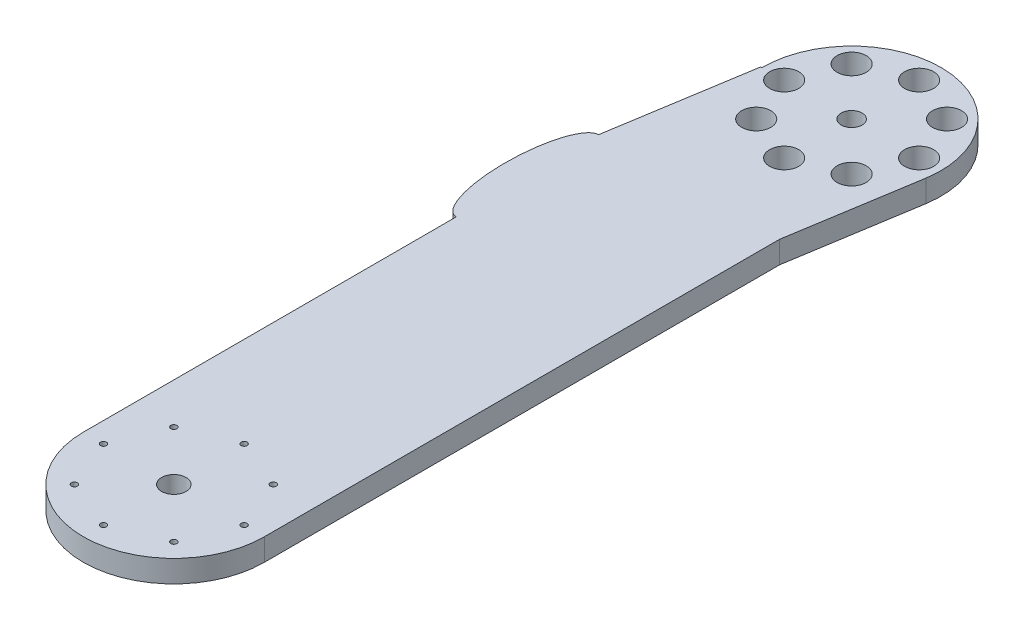
SolidWorks part; units mm, degrees
ref_plane "Plano frontal" through (0, 0, 0) normal (0, 0, 1) x (1, 0, 0)
ref_plane "Plano superior" through (0, 0, 0) normal (0, 1, 0) x (1, 0, 0)
ref_plane "Plano direito" through (0, 0, 0) normal (1, 0, 0) x (0, 0, -1)
sketch "Esboço1" plane through (0, 0, 0) normal (0, 1, 0) x (1, 0, 0)
  line L0 (-40.8421, 0) -> (-40.8421, 168.2347)
  line L1 (40.8421, 0) -> (40.8421, 168.2347)
  line L2 (40.8421, 232.4315) -> (51.0009, 295.8325)
  line L3 (40.8421, 168.2347) -> (40.8421, 232.4315)
  line L4 (-40.8421, 232.4315) -> (-30.751, 295.4098)
  line L5 (51.0009, 295.8325) -> (50.4521, 295.8297)
  line L6 (-30.2022, 295.4126) -> (-30.751, 295.4098)
  circle A0 centre (0, 0) radius 40.8421
  circle A11 centre (10.125, 295.6212) radius 40.3277
  ellipse E1 centre (-40.8421, 200.3331) end of major axis (-40.8421, 232.4315) minor radius 10.0911 (-40.8421, 232.4315) -> (-40.8421, 168.2347) ccw
  point P23 (0, 0)
  dimension "D2" = 81.6842
extrude "Ressalto-extrusão1" add sketch "Esboço1" along normal blind 10 contours L4 E1 L0 A0 L1 L3 L2 A11 L6 | A11 | A0 L2
sketch "Esboço7" plane through (0, 0, 0) normal (0, -1, 0) x (1, 0, 0)
  circle A2 centre (0, -31.7168) radius 1.35
  circle A3 centre (-22.4271, -22.4271) radius 1.35
  circle A4 centre (-31.7168, 0) radius 1.35
  circle A5 centre (-22.4271, 22.4271) radius 1.35
  circle A6 centre (0, 31.7168) radius 1.35
  circle A7 centre (22.4271, 22.4271) radius 1.35
  circle A8 centre (31.7168, 0) radius 1.35
  circle A9 centre (22.4271, -22.4271) radius 1.35
  point P0 (0, 0)
  point P20 (0, 0)
  dimension "D2" = 2.7
  dimension "D1" = 8
extrude "Corte-extrusão8" cut sketch "Esboço7" against normal up to next
sketch "Esboço8" plane through (0, 10, 0) normal (0, 1, 0) x (1, 0, 0)
  circle A0 centre (0, 0) radius 5.5
  dimension "D1" = 11
extrude "Corte-extrusão9" cut sketch "Esboço8" against normal up to next
sketch "Esboço9" plane through (0, 10, 0) normal (0, 1, 0) x (1, 0, 0)
  circle A1 centre (10.125, 295.6212) radius 30.4305
  circle A2 centre (10.125, 326.0517) radius 6.5613
  circle A3 centre (31.6426, 317.1388) radius 6.5613
  circle A4 centre (40.5555, 295.6212) radius 6.5613
  circle A5 centre (31.6426, 274.1036) radius 6.5613
  circle A6 centre (10.125, 265.1907) radius 6.5613
  circle A7 centre (-11.3926, 274.1036) radius 6.5613
  circle A8 centre (-20.3055, 295.6212) radius 6.5613
  circle A9 centre (-11.3926, 317.1388) radius 6.5613
  point P21 (10.125, 295.6212)
  dimension "D1" = 8
extrude "Corte-extrusão11" cut sketch "Esboço9" against normal up to next contours A1 A9 | A1 A9 | A6 | A5 | A4 | A3 | A2 | A8 | A7
sketch "Esboço11" plane through (0, 10, 0) normal (0, 1, 0) x (1, 0, 0)
  circle A0 centre (10.125, 295.6212) radius 4.721
extrude "Corte-extrusão12" cut sketch "Esboço11" against normal up to next
